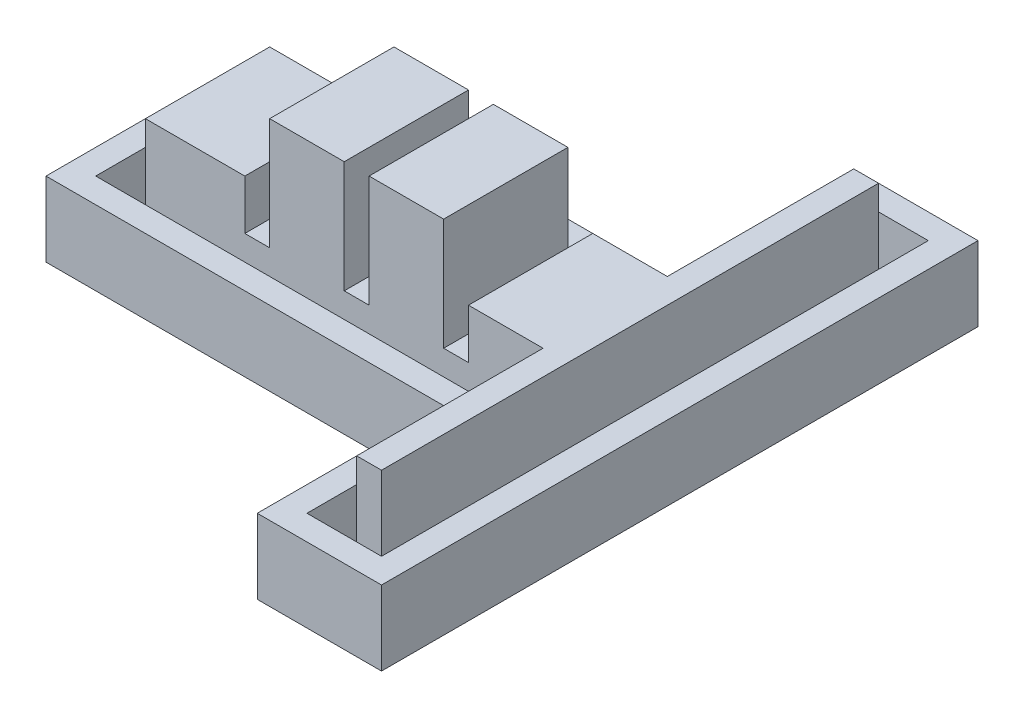
SolidWorks part; units mm, degrees
ref_plane "Front Plane" through (0, 0, 0) normal (0, 0, 1) x (1, 0, 0)
ref_plane "Top Plane" through (0, 0, 0) normal (0, 1, 0) x (1, 0, 0)
ref_plane "Right Plane" through (0, 0, 0) normal (1, 0, 0) x (0, 0, -1)
sketch "Sketch1" plane through (0, 0, 0) normal (0, 1, 0) x (1, 0, 0)
  line L1 (0, 0) -> (6, 0)
  line L2 (0, 0) -> (0, 10)
  line L3 (0, 10) -> (6, 10)
  line L4 (6, 0) -> (6, 10)
extrude "Boss-Extrude1" add sketch "Sketch1" along normal blind 13
sketch "Sketch2" plane through (0, 0, 0) normal (0, -1, 0) x (1, 0, 0)
  line L0 (6, 0) -> (6, -10) construction
  line L1 (5, -2) -> (1, -2)
  line L2 (5, -2) -> (5, -8)
  line L3 (5, -8) -> (1, -8)
  line L4 (1, -2) -> (1, -8)
  line L5 (0, -10) -> (0, 0) construction
  line L6 (0, 0) -> (6, 0) construction
  line L7 (6, -10) -> (0, -10) construction
  dimension "D1" = 1
  dimension "D2" = 1
  dimension "D3" = 2
  dimension "D4" = 2
extrude "Cut-Extrude1" cut sketch "Sketch2" against normal blind 11
sketch "Sketch3" plane through (0, 0, 0) normal (-1, 0, 0) x (0, 0, 1)
  line L0 (0, 13) -> (0, 0) construction
  line L1 (-10, 0) -> (0, 0)
  line L2 (-10, 0) -> (-10, 4)
  line L3 (-10, 4) -> (0, 4)
  line L4 (0, 0) -> (0, 4)
extrude "Boss-Extrude2" add sketch "Sketch3" along normal blind 2
pattern_linear "LPattern1" count 2 spacing 8 along (-1, 0, 0) of "Boss-Extrude2", "Boss-Extrude1", "Cut-Extrude1"
sketch "Sketch18" plane through (-10, 0, 0) normal (-1, 0, 0) x (0, 0, 1)
  line L1 (0, 0) -> (-10, 0)
  line L2 (0, 0) -> (0, 8)
  line L3 (0, 8) -> (-10, 8)
  line L4 (-10, 0) -> (-10, 8)
extrude "Boss-Extrude3" add sketch "Sketch18" along normal blind 8
sketch "Sketch20" plane through (6, 0, 0) normal (1, 0, 0) x (0, 0, -1)
  line L0 (10, 13) -> (10, 0) construction
  line L1 (0, 0) -> (10, 0)
  line L2 (0, 0) -> (0, 4)
  line L3 (0, 4) -> (10, 4)
  line L4 (10, 0) -> (10, 4)
extrude "Boss-Extrude4" add sketch "Sketch20" along normal blind 2
sketch "Sketch21" plane through (8, 0, 0) normal (1, 0, 0) x (0, 0, -1)
  line L1 (0, 0) -> (10, 0)
  line L2 (0, 0) -> (0, 8)
  line L3 (0, 8) -> (10, 8)
  line L4 (10, 0) -> (10, 8)
extrude "Boss-Extrude5" add sketch "Sketch21" along normal blind 6
sketch "Sketch22" plane through (14, 0, 0) normal (1, 0, 0) x (0, 0, -1)
  line L1 (0, 0) -> (10, 0) construction
  line L2 (0, 0) -> (0, 8) construction
  line L3 (0, 8) -> (10, 8) construction
  line L4 (10, 0) -> (10, 8) construction
  line L11 (25, 0) -> (25, 8)
  line L12 (-15, 8) -> (25, 8)
  line L13 (25, 0) -> (-15, 0)
  line L14 (-15, 0) -> (-15, 8)
  dimension "D1" = 15
  dimension "D2" = 15
extrude "Boss-Extrude6" add sketch "Sketch22" along normal blind 2
sketch "Sketch23" plane through (0, 0, 0) normal (0, -1, 0) x (1, 0, 0)
  line L0 (5, -8) -> (5, -2) construction
  line L1 (9, -2) -> (13, -2)
  line L2 (9, -2) -> (9, -8)
  line L3 (9, -8) -> (13, -8)
  line L4 (13, -2) -> (13, -8)
  line L5 (-2, 0) -> (14, 0) construction
  line L6 (-7, -2) -> (-7, -8) construction
  line L7 (-15, -2) -> (-11, -2)
  line L8 (-15, -2) -> (-15, -8)
  line L9 (-15, -8) -> (-11, -8)
  line L10 (-11, -2) -> (-11, -8)
  dimension "D1" = 4
  dimension "D2" = 2
  dimension "D3" = 4
extrude "Cut-Extrude2" cut sketch "Sketch23" against normal blind 6
combine bodies "Combine1" operation type add bodies to combine 135 136
sketch "Sketch33" plane through (0, 0, 0) normal (0, -1, 0) x (1, 0, 0)
  line L40 (12, 2) -> (-20, 2)
  line L41 (-20, 2) -> (-20, -12)
  line L42 (-20, -12) -> (12, -12)
  line L43 (12, -12) -> (12, -27)
  line L44 (12, -27) -> (18, -27)
  line L45 (18, -27) -> (18, 17)
  line L46 (18, 17) -> (12, 17)
  line L47 (12, 17) -> (12, 2)
  line L48 (12, 2) -> (-20, 2)
  line L49 (-20, 2) -> (-20, -12)
  line L50 (-20, -12) -> (12, -12)
  line L51 (12, -12) -> (12, -27)
  line L52 (12, -27) -> (18, -27)
  line L53 (18, -27) -> (18, 17)
  line L54 (18, 17) -> (12, 17)
  line L55 (12, 17) -> (12, 2)
  dimension "D2" = 2
extrude "Boss-Extrude15" add sketch "Sketch33" along normal blind 2 separate body contours L48 L49 L50 L51 L52 L53 L54 L55
sketch "Sketch34" plane through (0, -2, 0) normal (0, -1, 0) x (1, 0, 0)
  line L8 (10, 19) -> (10, 4)
  line L9 (10, 4) -> (-22, 4)
  line L10 (-22, 4) -> (-22, -14)
  line L11 (-22, -14) -> (10, -14)
  line L12 (10, -14) -> (10, -29)
  line L13 (10, -29) -> (20, -29)
  line L14 (20, -29) -> (20, 19)
  line L15 (20, 19) -> (10, 19)
  line L16 (12, 17) -> (12, 2)
  line L17 (12, 2) -> (-20, 2)
  line L18 (-20, 2) -> (-20, -12)
  line L19 (-20, -12) -> (12, -12)
  line L20 (12, -12) -> (12, -27)
  line L21 (12, -27) -> (18, -27)
  line L22 (18, -27) -> (18, 17)
  line L23 (18, 17) -> (12, 17)
  line L24 (12, 17) -> (12, 2)
  line L25 (12, 2) -> (-20, 2)
  line L26 (-20, 2) -> (-20, -12)
  line L27 (-20, -12) -> (12, -12)
  line L28 (12, -12) -> (12, -27)
  line L29 (12, -27) -> (18, -27)
  line L30 (18, -27) -> (18, 17)
  line L31 (18, 17) -> (12, 17)
  dimension "D1" = 0
  dimension "D2" = 2
extrude "Boss-Extrude16" add sketch "Sketch34" against normal blind 6
